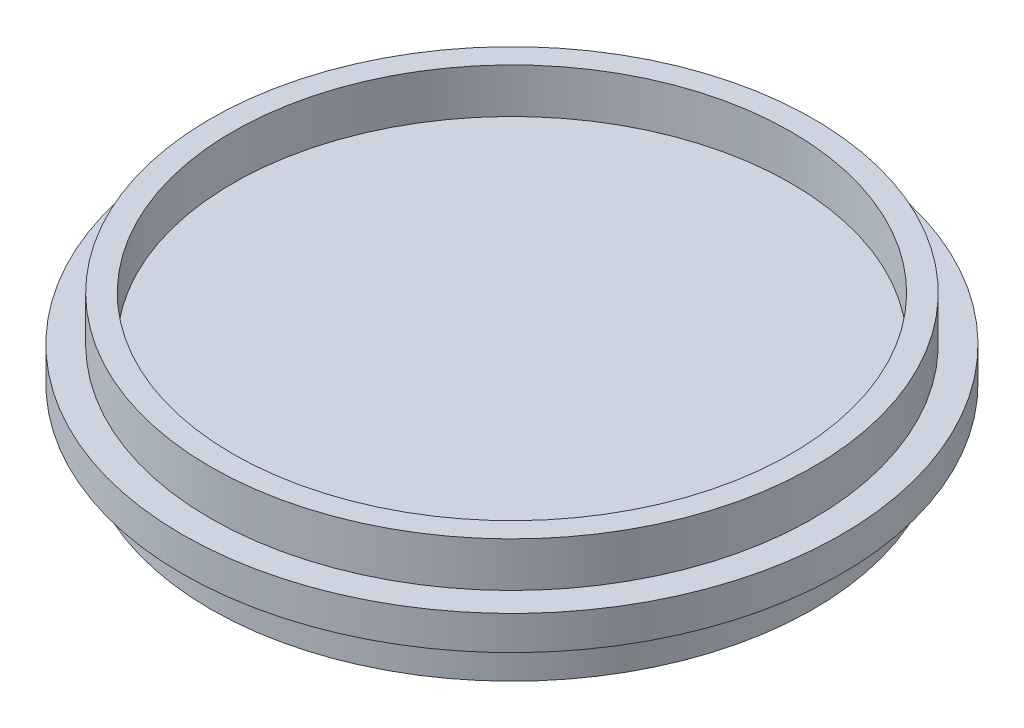
SolidWorks part; units mm, degrees
material "6061-T6 (SS)"
ref_plane "Front Plane" through (0, 0, 0) normal (0, 0, 1) x (1, 0, 0)
ref_plane "Top Plane" through (0, 0, 0) normal (0, 1, 0) x (1, 0, 0)
ref_plane "Right Plane" through (0, 0, 0) normal (1, 0, 0) x (0, 0, -1)
sketch "Sketch1" plane through (0, 0, 0) normal (0, 1, 0) x (1, 0, 0)
  circle A0 centre (0, 0) radius 93.726
  dimension "D1" = 187.452
extrude "Boss-Extrude1" add sketch "Sketch1" along normal mid plane 9.652
sketch "Sketch2" plane through (0, 0, 0) normal (0, 0, 1) x (1, 0, 0)
  line L0 (0, -18.3275) -> (0, 20.8308) construction
  line L1 (0, -4.826) -> (-19.297, -4.826)
  line L2 (-93.726, -4.826) -> (93.726, -4.826) construction
  line L3 (0, -4.826) -> (0, -1.4952)
  line L4 (-0.3818, -1.4952) -> (0, -1.4952)
  arc A0 (-19.297, -4.826) -> (-0.3818, -1.4952) centre (-0.4072, -56.7254) cw
  dimension "D6" = 55.2302
  dimension "D1" = 19.297
  dimension "D2" = 3.3308
  dimension "D3" = 0.3818
revolve "Cut-Revolve1" [suppressed] cut sketch "Sketch2" angle 360 about L0
sketch "Sketch4" plane through (0, 4.826, 0) normal (0, 1, 0) x (1, 0, 0)
  circle A0 centre (0, 0) radius 85.725
  circle A1 centre (0, 0) radius 79.375
  dimension "D1" = 171.45
  dimension "D2" = 158.75
extrude "Boss-Extrude2" add sketch "Sketch4" along normal blind 12.7
ref_plane "Plane1" through (0, 0, -85.725) normal (0, 0, -1) x (-1, 0, 0)
sketch "Sketch5" plane through (0, 0, -85.725) normal (0, 0, -1) x (-1, 0, 0)
  line L0 (0, 19.2786) -> (0, -19.2786) construction
  line L1 (79.375, 17.526) -> (-79.375, 17.526) construction
  circle A0 centre (0, 11.176) radius 1.4351
  dimension "D1" = 2.8702
  dimension "D2" = 6.35
extrude "Cut-Extrude2" [suppressed] cut sketch "Sketch5" against normal blind 12.7
pattern_circular "CirPattern1" [suppressed] count 12 over 360
mirror "Mirror2" about plane through (0, 0, 0) normal (0, 1, 0) of "Boss-Extrude2"
sketch "Sketch6" plane through (0, 4.826, 0) normal (0, 1, 0) x (1, 0, 0)
  line L0 (-63.5, 0) -> (-69.85, 0)
  line L1 (0, -69.85) -> (0, -63.5)
  line L2 (0, -19.2786) -> (0, 19.2786) construction
  arc A0 (-69.85, 0) -> (0, -69.85) centre (0, 0) ccw
  arc A1 (-63.5, 0) -> (0, -63.5) centre (0, 0) ccw
  dimension "D1" = 69.85
  dimension "D2" = 63.5
  dimension "D3" = 90
extrude "Cut-Extrude3" [suppressed] cut sketch "Sketch6" against normal up to surface (9.652 mm away)
